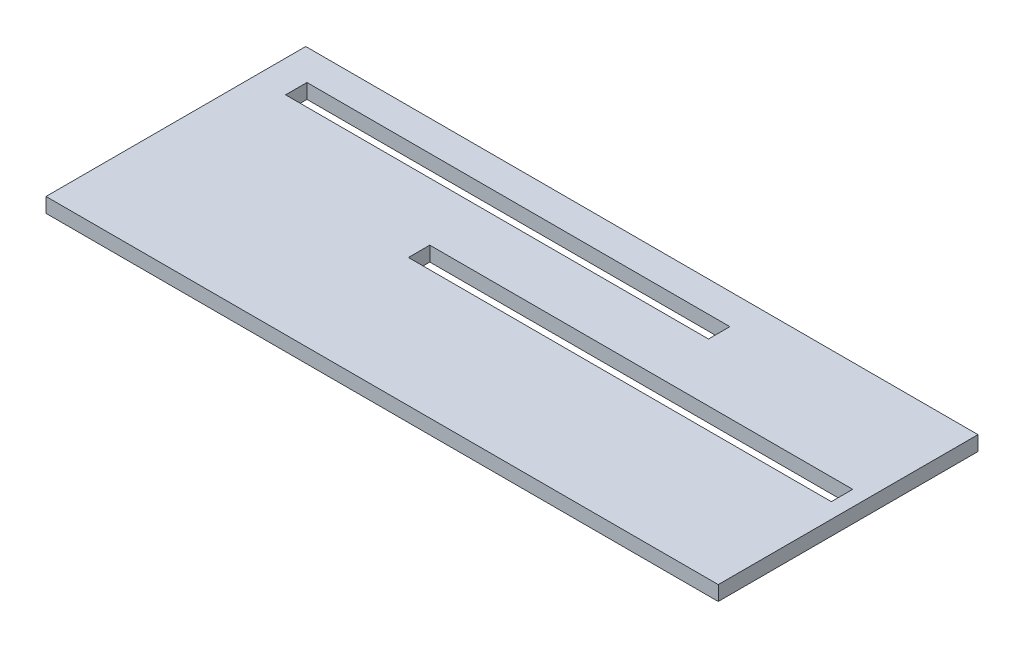
SolidWorks part; units mm, degrees
material "PBT General Purpose"
ref_plane "Front Plane" through (0, 0, 0) normal (0, 0, 1) x (1, 0, 0)
ref_plane "Top Plane" through (0, 0, 0) normal (0, 1, 0) x (1, 0, 0)
ref_plane "Right Plane" through (0, 0, 0) normal (1, 0, 0) x (0, 0, -1)
sketch "Sketch1" plane through (0, 0, 0) normal (0, 1, 0) x (1, 0, 0)
  line L0 (0, 0) -> (0, 4.25)
  line L1 (0, 4.25) -> (11, 4.25)
  line L2 (11, 4.25) -> (11, 0)
  line L3 (11, 0) -> (0, 0)
  line L4 (0.52, 3.75) -> (0.52, 3.4)
  line L5 (0.52, 3.4) -> (7.44, 3.4)
  line L6 (7.44, 3.4) -> (7.44, 3.75)
  line L7 (7.44, 3.75) -> (0.52, 3.75)
  line L8 (3.83, 2.45) -> (3.83, 2.1)
  line L9 (3.83, 2.1) -> (10.75, 2.1)
  line L10 (10.75, 2.1) -> (10.75, 2.45)
  line L11 (10.75, 2.45) -> (3.83, 2.45)
  point P12 (0, 0)
  point P14 (0, 0)
  point P15 (0, 0)
  point P16 (0, 0)
  point P17 (0, 0)
  point P18 (0, 0)
  point P19 (0, 0)
  point P20 (0, 0)
  dimension "D1" = 6.92
  dimension "D2" = 6.92
  dimension "D3" = 0.35
  dimension "D4" = 0.35
  dimension "D5" = 0.95
  dimension "D6" = 3.61
  dimension "D7" = 2.1
  dimension "D8" = 0.5
  dimension "D9" = 0.25
  dimension "D10" = 0.52
extrude "Boss-Extrude1" add sketch "Sketch1" along normal blind 0.24
